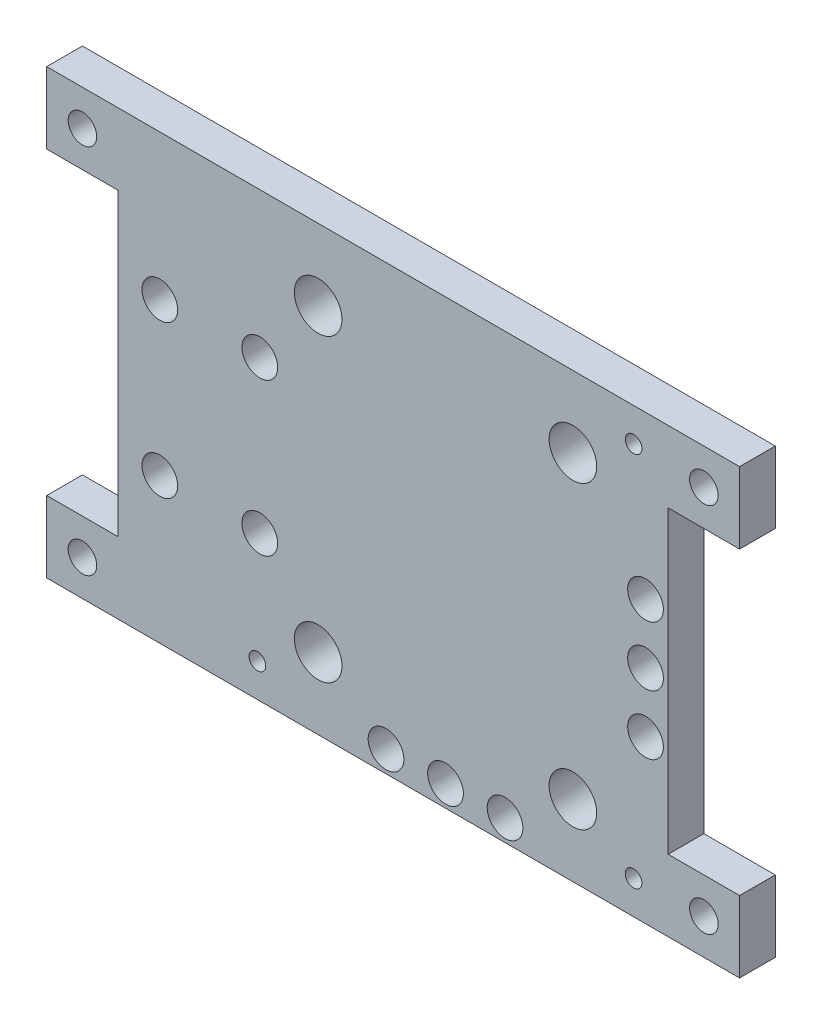
SolidWorks part; units mm, degrees
ref_plane "前视基准面" through (0, 0, 0) normal (0, 0, 1) x (1, 0, 0)
ref_plane "上视基准面" through (0, 0, 0) normal (0, 1, 0) x (1, 0, 0)
ref_plane "右视基准面" through (0, 0, 0) normal (1, 0, 0) x (0, 0, -1)
other "Configuration Table"
sketch "草图1" plane through (0, 0, 0) normal (0, 0, 1) x (1, 0, 0)
  line L5 (-11.55, 9.3) -> (11.55, 9.3)
  line L6 (-11.55, 9.3) -> (-11.55, -9.3)
  line L7 (-11.55, -9.3) -> (11.55, -9.3)
  line L8 (11.55, 9.3) -> (11.55, -9.3)
  point P4 (0, 9.3)
  point P12 (-11.55, 0)
  dimension "D3" = 23.1
  dimension "D4" = 18.6
extrude "凸台-拉伸1" add sketch "草图1" along normal blind 1.5 contours L6 L7 L8 L5
sketch "草图2" plane through (0, 0, 0) normal (0, 0, -1) x (-1, 0, 0)
  circle A0 centre (-10.6, 2.5) radius 0.75
  circle A1 centre (-10.6, 0) radius 0.75
  circle A2 centre (-10.6, -2.5) radius 0.75
  circle A3 centre (-7.55, -6.3) radius 1
  circle A4 centre (3.15, -6.3) radius 1
  circle A5 centre (-4.7, -8.4) radius 0.75
  circle A6 centre (-2.2, -8.4) radius 0.75
  circle A7 centre (0.3, -8.4) radius 0.75
  circle A8 centre (-7.55, 6.3) radius 1
  circle A9 centre (3.15, 6.3) radius 1
  circle A10 centre (5.6, 3.2) radius 0.75
  circle A11 centre (9.8, 3.2) radius 0.75
  circle A12 centre (5.6, -3.2) radius 0.75
  circle A13 centre (9.8, -3.2) radius 0.75
  circle A14 centre (5.7, -7.9) radius 0.35
  circle A15 centre (-10.1, -7.9) radius 0.35
  circle A16 centre (-10.1, 7.9) radius 0.35
  dimension "D1" = 0.7
  dimension "D2" = 2
  dimension "D3" = 1.5
extrude "切除-拉伸1" cut sketch "草图2" against normal through all contours A15 | A3 | A2 | A1 | A0 | A8 | A16 | A9 | A10 | A11 | A13 | A12 | A4 | A14 | A7 | A6 | A5
sketch "草图3" plane through (0, 0, 0) normal (0, 0, -1) x (-1, 0, 0)
  line L1 (-11.55, 9.3) -> (-14.55, 9.3)
  line L2 (-11.55, 9.3) -> (-11.55, 6.3)
  line L3 (-11.55, 6.3) -> (-14.55, 6.3)
  line L4 (-14.55, 9.3) -> (-14.55, 6.3)
  line L5 (-11.55, -9.3) -> (-14.55, -9.3)
  line L6 (-11.55, -9.3) -> (-11.55, -6.3)
  line L7 (-11.55, -6.3) -> (-14.55, -6.3)
  line L8 (-14.55, -9.3) -> (-14.55, -6.3)
  line L9 (11.55, 9.3) -> (14.55, 9.3)
  line L10 (11.55, 9.3) -> (11.55, 6.3)
  line L11 (11.55, 6.3) -> (14.55, 6.3)
  line L12 (14.55, 9.3) -> (14.55, 6.3)
  line L13 (11.55, -9.3) -> (14.55, -9.3)
  line L14 (11.55, -9.3) -> (11.55, -6.3)
  line L15 (11.55, -6.3) -> (14.55, -6.3)
  line L16 (14.55, -9.3) -> (14.55, -6.3)
  circle A0 centre (-13.05, 7.8) radius 1
  circle A1 centre (-13.05, -7.8) radius 1
  circle A2 centre (13.05, -7.8) radius 1
  circle A3 centre (13.05, -7.8) radius 0.6
  circle A4 centre (13.05, 7.8) radius 1
  circle A5 centre (13.05, 7.8) radius 0.6
  circle A6 centre (-13.05, -7.8) radius 0.6
  circle A7 centre (-13.05, 7.8) radius 0.6
  point P32 (-13.05, -9.3)
  point P33 (-14.55, -7.8)
  point P35 (13.05, 9.3)
  point P36 (14.55, 7.8)
  dimension "D3" = 1.2
  dimension "D4" = 2
  dimension "D1" = 3
  dimension "D2" = 3
extrude "凸台-拉伸2" add sketch "草图3" against normal blind 1.5 contours L5 L8 L7 L6 | L3 L4 L1 L2 | L11 L12 L9 L10 | L15 L16 L13 L14 | A6 | A7 | A5 | A3
